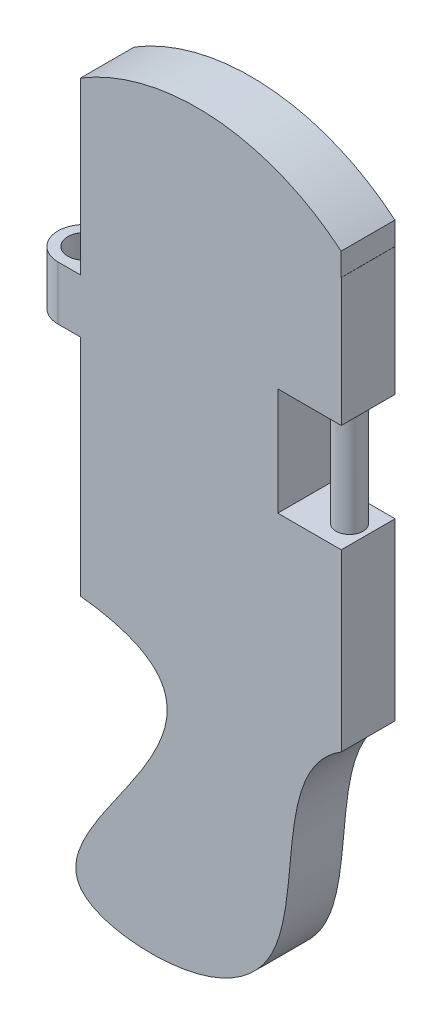
SolidWorks part; units mm, degrees
ref_plane "Alzado" through (0, 0, 0) normal (0, 0, 1) x (1, 0, 0)
ref_plane "Planta" through (0, 0, 0) normal (0, 1, 0) x (1, 0, 0)
ref_plane "Vista lateral" through (0, 0, 0) normal (1, 0, 0) x (0, 0, -1)
sketch "Croquis1" plane through (0, 0, 0) normal (0, 0, 1) x (1, 0, 0)
  line L0 (0, 0) -> (0, 50)
  line L2 (30, 0) -> (30, 47)
  arc A0 (0, 50) -> (30, 47) centre (13.0155, 28.6553) cw
  spline S0 degree 3 poles (0, 0) (23.8721, -2.7432) (-15.1561, -28.8208) (12.5645, -31.6225) (27.1084, -22.1344) (20.6835, -4.6099) (30, 0) knots 0 0 0 0 0.411785 0.564961 0.677133 1 1 1 1
  dimension "D3" = 25
  dimension "D1" = 50
  dimension "D2" = 30
  dimension "D4" = 47
extrude "Saliente-Extruir1" add sketch "Croquis1" along normal blind 6
sketch "Croquis2" plane through (0, 0, 0) normal (0, 1, 0) x (1, 0, 0)
  line L0 (30, 0) -> (-0.5083, 0) construction
  line L1 (-0.5083, -6) -> (30, -6) construction
  line L4 (0, -6) -> (0, 0) construction
  line L5 (-2.5, 0) -> (0, 0)
  line L7 (-2.5, -6) -> (0, -6)
  line L8 (0, 0) -> (0, -6)
  arc A0 (-2.5, 0) -> (-2.5, -6) centre (-2.5, -3) ccw
  dimension "D1" = 2.5
  dimension "D2" = 0
extrude "Saliente-Extruir3" add sketch "Croquis2" along normal blind 6 from offset 25
sketch "Croquis4" plane through (0, 31, 0) normal (0, 1, 0) x (1, 0, 0)
  line L0 (0, 0) -> (-2.5, 0) construction
  line L1 (0, -6) -> (0, 0) construction
  circle A0 centre (-2.5, -3) radius 1.9
  dimension "D1" = 3.8
  dimension "D2" = 3
  dimension "D3" = 2.5
extrude "Cortar-Extruir1" cut sketch "Croquis4" against normal blind 6
sketch "Croquis5" plane through (0, 0, 6) normal (0, 0, 1) x (1, 0, 0)
  line L0 (30, 0) -> (30, 47) construction
  line L1 (30, 31) -> (22, 31)
  line L2 (30, 31) -> (30, 19)
  line L3 (30, 19) -> (22, 19)
  line L4 (22, 31) -> (22, 19)
  dimension "D1" = 12
  dimension "D2" = 8
  dimension "D3" = 19
extrude "Cortar-Extruir2" cut sketch "Croquis5" against normal blind 6
sketch "Croquis6" plane through (0, 19, 0) normal (0, 1, 0) x (1, 0, 0)
  line L0 (22, 0) -> (30, 0) construction
  line L1 (30, 0) -> (30, -6) construction
  circle A0 centre (27, -3) radius 1.5
  dimension "D1" = 3
  dimension "D2" = 3
  dimension "D3" = 3
extrude "Saliente-Extruir4" add sketch "Croquis6" along normal up to next
sketch "Croquis7" plane through (0, 0, 6) normal (0, 0, 1) x (1, 0, 0)
  line L1 (30, 47) -> (29.0753, 47)
  line L2 (30, 47) -> (30, -1.4948)
  line L3 (30, -1.4948) -> (29.0753, -1.4948)
  line L4 (29.0753, 47) -> (29.0753, -1.4948)
extrude "Cortar-Extruir3" cut sketch "Croquis7" against normal blind 10
sketch "Croquis9" plane through (0, 0, 6) normal (0, 0, 1) x (1, 0, 0)
  line L1 (29.0596, 47.8279) -> (30.4569, 47.8279)
  line L2 (29.0596, 47.8279) -> (29.0596, 45.2789)
  line L3 (29.0596, 45.2789) -> (30.4569, 45.2789)
  line L4 (30.4569, 47.8279) -> (30.4569, 45.2789)
  arc A0 (30, 47) -> (0, 50) centre (13.0155, 28.6553) ccw construction
extrude "Cortar-Extruir4" cut sketch "Croquis9" against normal blind 6
